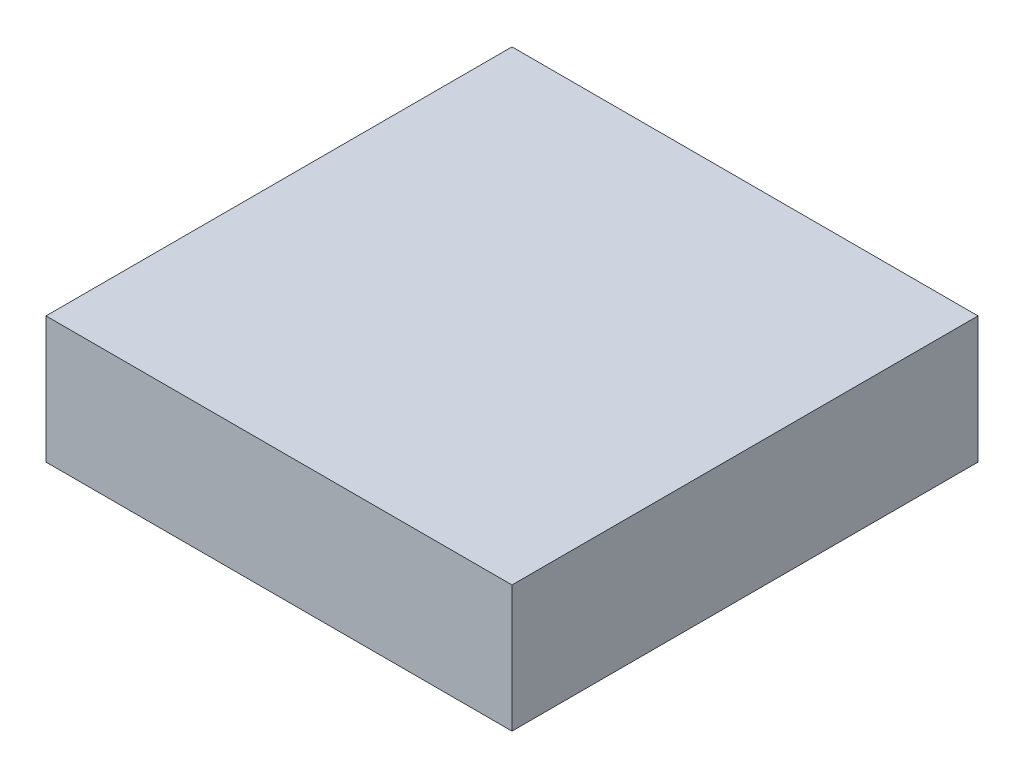
SolidWorks part; units mm, degrees
ref_plane "前视基准面" through (0, 0, 0) normal (0, 0, 1) x (1, 0, 0)
ref_plane "上视基准面" through (0, 0, 0) normal (0, 1, 0) x (1, 0, 0)
ref_plane "右视基准面" through (0, 0, 0) normal (1, 0, 0) x (0, 0, -1)
sketch "草图1" plane through (0, 0, 0) normal (0, 1, 0) x (1, 0, 0)
  line L1 (0, 0) -> (92, 0)
  line L2 (0, 0) -> (0, 92)
  line L3 (0, 92) -> (92, 92)
  line L4 (92, 0) -> (92, 92)
  dimension "D1" = 92
  dimension "D2" = 92
extrude "凸台-拉伸1" add sketch "草图1" along normal blind 25
